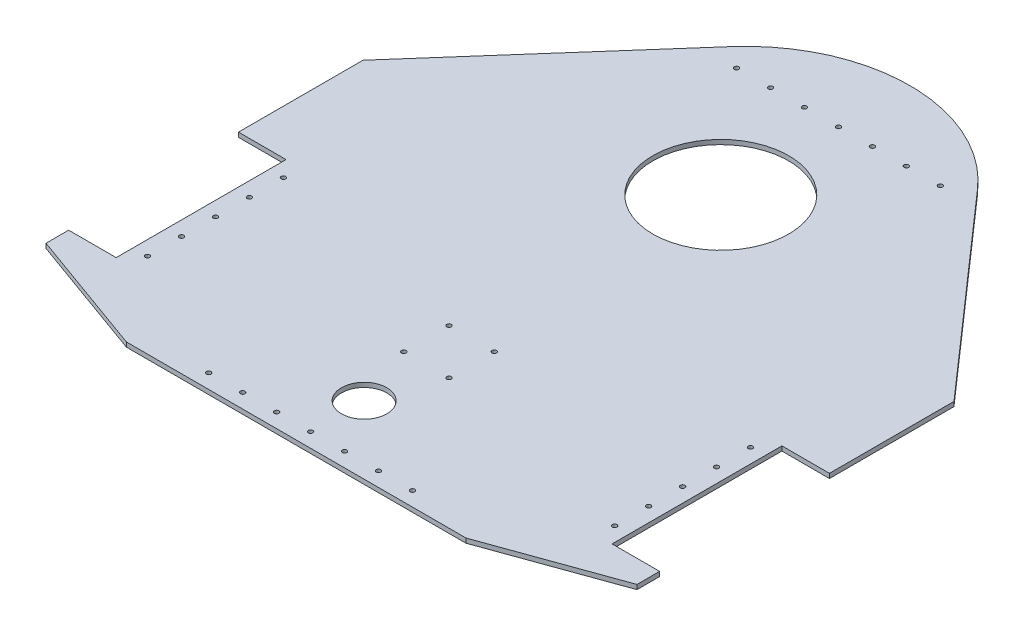
SolidWorks part; units mm, degrees
ref_plane "Front Plane" through (0, 0, 0) normal (0, 0, 1) x (1, 0, 0)
ref_plane "Top Plane" through (0, 0, 0) normal (0, 1, 0) x (1, 0, 0)
ref_plane "Right Plane" through (0, 0, 0) normal (1, 0, 0) x (0, 0, -1)
sketch "Sketch1" plane through (0, 0, 0) normal (0, 1, 0) x (1, 0, 0)
  line L0 (-240, -25) -> (240, -25) construction
  line L1 (240, -25) -> (0, 215) construction
  line L2 (0, 215) -> (-240, -25) construction
  line L3 (0, 215) -> (0, -25) construction
  line L6 (-219, 50) -> (-219, -100)
  line L7 (-219, -100) -> (-261, -100)
  line L8 (-261, -100) -> (-261, -120)
  line L10 (-150, -160) -> (150, -160)
  line L11 (-219, 50) -> (-261, 50)
  line L12 (-261, 50) -> (-261, 160)
  line L13 (-261, 160) -> (-110, 331.6587)
  line L14 (-150, -160) -> (-261, -120)
  line L15 (261, 160) -> (110, 331.6587)
  line L16 (150, -160) -> (261, -120)
  line L18 (261, -100) -> (261, -120)
  line L19 (219, -100) -> (261, -100)
  line L20 (219, 50) -> (219, -100)
  line L21 (219, 50) -> (261, 50)
  line L22 (261, 50) -> (261, 160)
  circle A3 centre (0, 215) radius 60
  arc A7 (110, 331.6587) -> (-110, 331.6587) centre (0, 237.0979) ccw
  point P29 (0, 331.6587)
  dimension "D1" = 480
  dimension "D4" = 75
  dimension "D6" = 120
  dimension "D7" = 42
  dimension "D2" = 240
  dimension "D3" = 21
  dimension "D5" = 75
  dimension "D8" = 20
  dimension "D9" = 300
  dimension "D10" = 42
  dimension "D11" = 110
  dimension "D12" = 110
  dimension "D13" = 21
  dimension "D14" = 21
  dimension "D15" = 150
extrude "Boss-Extrude1" add sketch "Sketch1" along normal blind 4
sketch "Sketch2" plane through (0, 4, 0) normal (0, 1, 0) x (1, 0, 0)
  line L0 (-219, -25) -> (219, -25) construction
  line L1 (-219, 50) -> (-219, -100) construction
  line L2 (219, 50) -> (219, -100) construction
  line L3 (0, -100) -> (0, -160) construction
  line L5 (-150, -160) -> (150, -160) construction
  circle A0 centre (-206.3, -25) radius 2
  circle A1 centre (-206.3, 5) radius 2
  circle A2 centre (-206.3, 35) radius 2
  circle A3 centre (-206.3, -55) radius 2
  circle A4 centre (-206.3, -85) radius 2
  circle A5 centre (206.3, -85) radius 2
  circle A6 centre (206.3, -55) radius 2
  circle A7 centre (206.3, 5) radius 2
  circle A8 centre (206.3, 35) radius 2
  circle A9 centre (206.3, -25) radius 2
  circle A10 centre (0, -100) radius 20
  dimension "D1" = 12.7
  dimension "D4" = 60
  dimension "D2" = 3
  dimension "D3" = 3
extrude "Cut-Extrude1" cut sketch "Sketch2" against normal up to surface (4 mm away) up to face at (0, 0, -155)
sketch "Sketch3" plane through (0, 4, 0) normal (0, 1, 0) x (1, 0, 0)
  line L0 (-110, 331.6587) -> (110, 331.6587) construction
  line L1 (0, 331.6587) -> (0, 297.4676) construction
  line L2 (-150, -160) -> (150, -160) construction
  circle A0 centre (0, 318.9587) radius 2
  circle A1 centre (30, 318.9587) radius 2
  circle A2 centre (60, 318.9587) radius 2
  circle A3 centre (90, 318.9587) radius 2
  circle A4 centre (-30, 318.9587) radius 2
  circle A5 centre (-60, 318.9587) radius 2
  circle A6 centre (-90, 318.9587) radius 2
  circle A7 centre (0, -147.3) radius 2
  circle A8 centre (30, -147.3) radius 2
  circle A9 centre (60, -147.3) radius 2
  circle A10 centre (90, -147.3) radius 2
  circle A11 centre (-30, -147.3) radius 2
  circle A12 centre (-60, -147.3) radius 2
  circle A13 centre (-90, -147.3) radius 2
  dimension "D1" = 12.7
  dimension "D4" = 12.7
  dimension "D2" = 4
  dimension "D3" = 4
  dimension "D5" = 4
  dimension "D6" = 4
extrude "Cut-Extrude2" cut sketch "Sketch3" against normal up to surface (4 mm away) up to face at (-206.3, 0, -3)
sketch "Sketch4" plane through (0, 4, 0) normal (0, 1, 0) x (1, 0, 0)
  line L0 (-219, -25) -> (219, -25) construction
  line L1 (-219, 50) -> (-219, -100) construction
  line L2 (219, 50) -> (219, -100) construction
  line L3 (0, -25) -> (0, 215) construction
  circle A0 centre (-20, -5) radius 2
  circle A1 centre (20, -5) radius 2
  circle A2 centre (20, -45) radius 2
  circle A3 centre (-20, -45) radius 2
  point P20 (0, -25)
  dimension "D1" = 20
  dimension "D2" = 20
  dimension "D3" = 4
extrude "Cut-Extrude3" cut sketch "Sketch4" against normal up to surface (4 mm away) up to face at (30, 0, 149.3)
